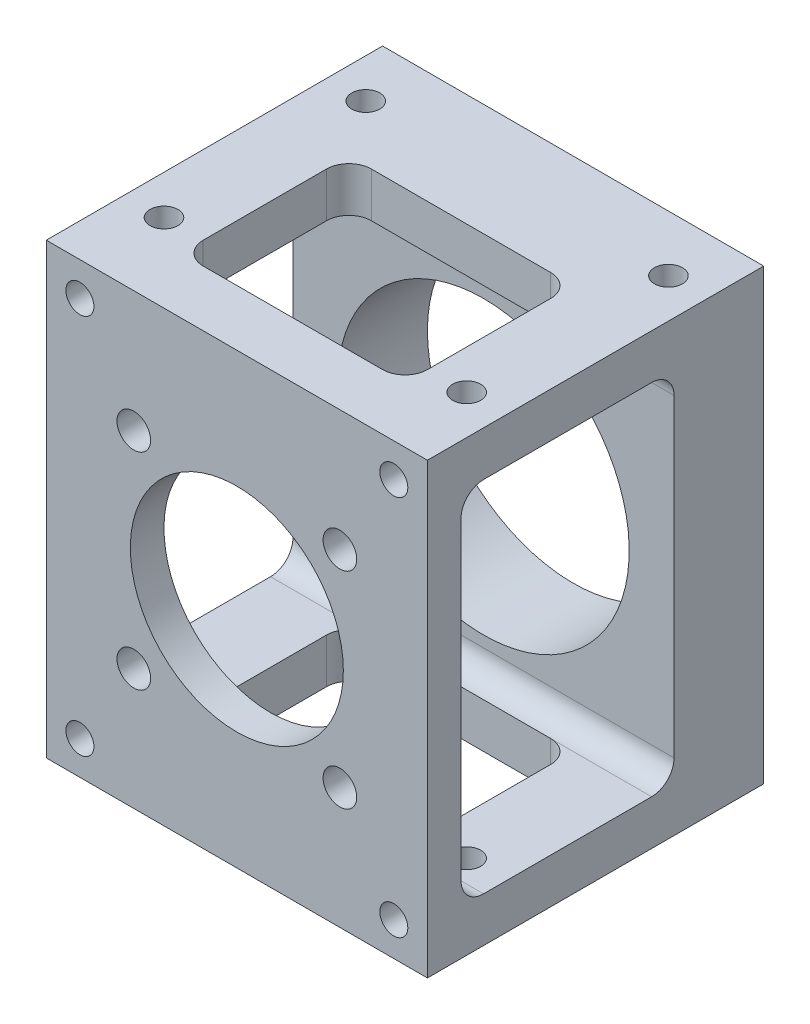
SolidWorks part; units mm, degrees
material "6061-T6 (SS)"
ref_plane "前视基准面" through (0, 0, 0) normal (0, 0, 1) x (1, 0, 0)
ref_plane "上视基准面" through (0, 0, 0) normal (0, 1, 0) x (1, 0, 0)
ref_plane "右视基准面" through (0, 0, 0) normal (1, 0, 0) x (0, 0, -1)
sketch "草图1" plane through (0, 0, 0) normal (0, 0, 1) x (1, 0, 0)
  line L0 (17, 0) -> (17, 20) construction
  line L1 (0, 0) -> (34, 0)
  line L2 (0, 0) -> (0, 40)
  line L3 (0, 40) -> (34, 40)
  line L4 (34, 0) -> (34, 40)
  circle A0 centre (17, 20) radius 9.5
  dimension "D3" = 19
  dimension "D1" = 34
  dimension "D2" = 40
  dimension "D4" = 20
extrude "凸台-拉伸1" add sketch "草图1" along normal blind 30
sketch "草图3" plane through (0, 0, 0) normal (-1, 0, 0) x (0, 0, 1)
  line L0 (0, 20) -> (17.5, 20) construction
  line L1 (0, 40) -> (0, 0) construction
  line L9 (30, 40) -> (30, 0) construction
  line L10 (8, 36) -> (27, 36)
  line L11 (8, 36) -> (8, 4)
  line L12 (8, 4) -> (27, 4)
  line L13 (27, 36) -> (27, 4)
  line L14 (8, 36) -> (27, 4) construction
  line L15 (8, 4) -> (27, 36) construction
  dimension "D1" = 19
  dimension "D2" = 32
  dimension "D5" = 3
extrude "切除-拉伸1" cut sketch "草图3" against normal through all
fillet "圆角3" radius 2 4 edges at (17, 36, 8) (17, 36, 27) (17, 4, 27) (17, 4, 8)
sketch "草图10" plane through (0, 40, 0) normal (0, 1, 0) x (1, 0, 0)
  line L0 (17, 0) -> (17, -14) construction
  line L1 (34, 0) -> (0, 0) construction
  line L2 (34, -30) -> (34, 0) construction
  line L3 (3.5, -5) -> (30.5, -5) construction
  line L4 (3.5, -5) -> (3.5, -23) construction
  line L5 (3.5, -23) -> (30.5, -23) construction
  line L6 (30.5, -5) -> (30.5, -23) construction
  line L7 (3.5, -5) -> (30.5, -23) construction
  line L8 (3.5, -23) -> (30.5, -5) construction
  circle A0 centre (30.5, -5) radius 1.5
  circle A1 centre (30.5, -23) radius 1.5
  circle A2 centre (3.5, -23) radius 1.5
  circle A3 centre (3.5, -5) radius 1.5
  dimension "D4" = 3
  dimension "D1" = 3.5
  dimension "D2" = 5
  dimension "D3" = 18
sketch "草图21" plane through (0, 0, 0) normal (0, -1, 0) x (1, 0, 0)
  circle A1 centre (3.5, 5) radius 1.5
  circle A2 centre (3.5, 5) radius 1.5
  circle A3 centre (3.5, 23) radius 1.5
  circle A4 centre (3.5, 23) radius 1.5
  circle A5 centre (30.5, 23) radius 1.5
  circle A6 centre (30.5, 23) radius 1.5
  circle A7 centre (30.5, 5) radius 1.5
  circle A8 centre (30.5, 5) radius 1.5
  dimension "D1" = 0
  dimension "D2" = 0
  dimension "D3" = 0
  dimension "D4" = 0
hole_wizard "M3 螺纹孔2" positions "3D草图2" profile "草图11" tap size "M3" standard "GB"
sketch3d "3D草图2"
  point P0 (3.5, 40, 5)
  point P3 (30.5, 40, 5)
  point P6 (30.5, 40, 23)
  point P9 (3.5, 40, 23)
cosmetic thread "孔螺蚊线5" parameters "D1"=4, "D2"=3
cosmetic thread "孔螺蚊线6" parameters "D1"=4, "D2"=3
cosmetic thread "孔螺蚊线7" parameters "D1"=4, "D2"=3
cosmetic thread "孔螺蚊线8" parameters "D1"=4, "D2"=3
sketch "草图11" plane through (3.5, 40, 5) normal (1, 0, 0) x (0, 0, 1)
  line L0 (0, 0) -> (0, 4.7511)
  line L1 (0, 4.7511) -> (1.25, 4)
  line L2 (1.25, 4) -> (1.25, 0)
  line L5 (1.25, 0) -> (0, 0)
  line L10 (0, 4.7511) -> (-1.25, 4) construction
  line L11 (0, -6.35) -> (0, 107.95) construction
  dimension "螺纹孔钻头直径" = 2.5
  dimension "螺纹孔钻头深度" = 4
  dimension "导头角度" = 118
hole_wizard "M3 螺纹孔4" positions "3D草图5" profile "草图22" tap size "M3" standard "GB"
sketch3d "3D草图5"
  point P0 (3.5, 0, 5)
  point P3 (3.5, 0, 23)
  point P6 (30.5, 0, 23)
  point P9 (30.5, 0, 5)
cosmetic thread "孔螺蚊线13" parameters "D1"=4, "D2"=3
cosmetic thread "孔螺蚊线15" parameters "D1"=4, "D2"=3
sketch "草图22" plane through (3.5, 0, 5) normal (1, 0, 0) x (0, 0, -1)
  line L0 (0, 0) -> (0, 4.7511)
  line L1 (0, 4.7511) -> (1.25, 4)
  line L2 (1.25, 4) -> (1.25, 0)
  line L5 (1.25, 0) -> (0, 0)
  line L10 (0, 4.7511) -> (-1.25, 4) construction
  line L11 (0, -6.35) -> (0, 107.95) construction
  dimension "螺纹孔钻头直径" = 2.5
  dimension "螺纹孔钻头深度" = 4
  dimension "导头角度" = 118
cosmetic thread "孔螺蚊线19" parameters "D1"=4, "D2"=3
cosmetic thread "孔螺蚊线20" parameters "D1"=4, "D2"=3
sketch "草图18" plane through (0, 40, 0) normal (0, 1, 0) x (1, 0, 0)
  line L0 (17, 0) -> (17, -34.9961) construction
  line L2 (7, -10) -> (27, -10)
  line L3 (7, -10) -> (7, -25)
  line L4 (7, -25) -> (27, -25)
  line L11 (27, -10) -> (27, -25)
  line L12 (7, -10) -> (27, -25) construction
  line L13 (7, -25) -> (27, -10) construction
  line L14 (34, 0) -> (0, 0) construction
  point P2 (17, -17.5)
  dimension "D3" = 10
  dimension "D4" = 20
  dimension "D5" = 15
extrude "切除-拉伸8" cut sketch "草图18" against normal through all
sketch "草图12" plane through (0, 0, 0) normal (0, 0, -1) x (-1, 0, 0)
  circle A0 centre (-17, 20) radius 13
  dimension "D1" = 26
extrude "切除-拉伸6" cut sketch "草图12" against normal up to surface (8 mm away) up to face at (17, 29.5, 8)
sketch "草图13" plane through (0, 0, 30) normal (0, 0, 1) x (1, 0, 0)
  line L1 (7.8076, 29.1924) -> (26.1924, 29.1924) construction
  line L2 (7.8076, 29.1924) -> (7.8076, 10.8076) construction
  line L3 (7.8076, 10.8076) -> (26.1924, 10.8076) construction
  line L4 (26.1924, 29.1924) -> (26.1924, 10.8076) construction
  line L5 (7.8076, 29.1924) -> (26.1924, 10.8076) construction
  line L6 (7.8076, 10.8076) -> (26.1924, 29.1924) construction
  circle A0 centre (26.1924, 10.8076) radius 1.5
  circle A1 centre (26.1924, 29.1924) radius 1.5
  circle A2 centre (7.8076, 29.1924) radius 1.5
  circle A3 centre (7.8076, 10.8076) radius 1.5
  point P0 (17, 20)
  dimension "D2" = 3
  dimension "D1" = 26
hole_wizard "Ø3.0 (3) 直径孔1" positions "3D草图3" profile "草图14" hole size "Ø3.0" standard "GB"
sketch3d "3D草图3"
  point P0 (7.8076, 29.1924, 30)
  point P3 (26.1924, 29.1924, 30)
  point P6 (26.1924, 10.8076, 30)
  point P9 (7.8076, 10.8076, 30)
sketch "草图14" plane through (7.8076, 29.1924, 30) normal (1, 0, 0) x (0, -1, 0)
  line L0 (0, 0) -> (0, 3)
  line L1 (0, 3) -> (1.5, 3)
  line L2 (1.5, 3) -> (1.5, 0)
  line L5 (1.5, 0) -> (0, 0)
  line L11 (0, -6.35) -> (0, 107.95) construction
  dimension "通孔孔直径" = 3
  dimension "通孔孔深度" = 3
fillet "圆角7" radius 2 8 edges at (27, 2, 25) (7, 2, 25) (7, 2, 10) (27, 2, 10) (7, 38, 10) (27, 38, 10) (7, 38, 25) (27, 38, 25)
sketch "草图19" plane through (0, 0, 30) normal (0, 0, 1) x (1, 0, 0)
  line L1 (3, 37) -> (31, 37) construction
  line L2 (3, 37) -> (3, 3) construction
  line L3 (3, 3) -> (31, 3) construction
  line L4 (31, 37) -> (31, 3) construction
  line L5 (3, 37) -> (31, 3) construction
  line L6 (3, 3) -> (31, 37) construction
  point P0 (17, 20)
  dimension "D1" = 34
  dimension "D2" = 28
hole_wizard "M3 螺纹孔3" positions "3D草图4" profile "草图20" tap size "M3" standard "GB"
sketch3d "3D草图4"
  point P0 (3, 37, 30)
  point P3 (31, 37, 30)
  point P6 (31, 3, 30)
  point P9 (3, 3, 30)
sketch "草图20" plane through (3, 37, 30) normal (1, 0, 0) x (0, -1, 0)
  line L0 (0, 0) -> (0, 4.7511)
  line L1 (0, 4.7511) -> (1.25, 4)
  line L2 (1.25, 4) -> (1.25, 0)
  line L5 (1.25, 0) -> (0, 0)
  line L10 (0, 4.7511) -> (-1.25, 4) construction
  line L11 (0, -6.35) -> (0, 107.95) construction
  dimension "螺纹孔钻头直径" = 2.5
  dimension "螺纹孔钻头深度" = 4
  dimension "导头角度" = 118
cosmetic thread "孔螺蚊线9" parameters "D1"=4, "D2"=3
cosmetic thread "孔螺蚊线10" parameters "D1"=4, "D2"=3
cosmetic thread "孔螺蚊线11" parameters "D1"=4, "D2"=3
cosmetic thread "孔螺蚊线12" parameters "D1"=4, "D2"=3
